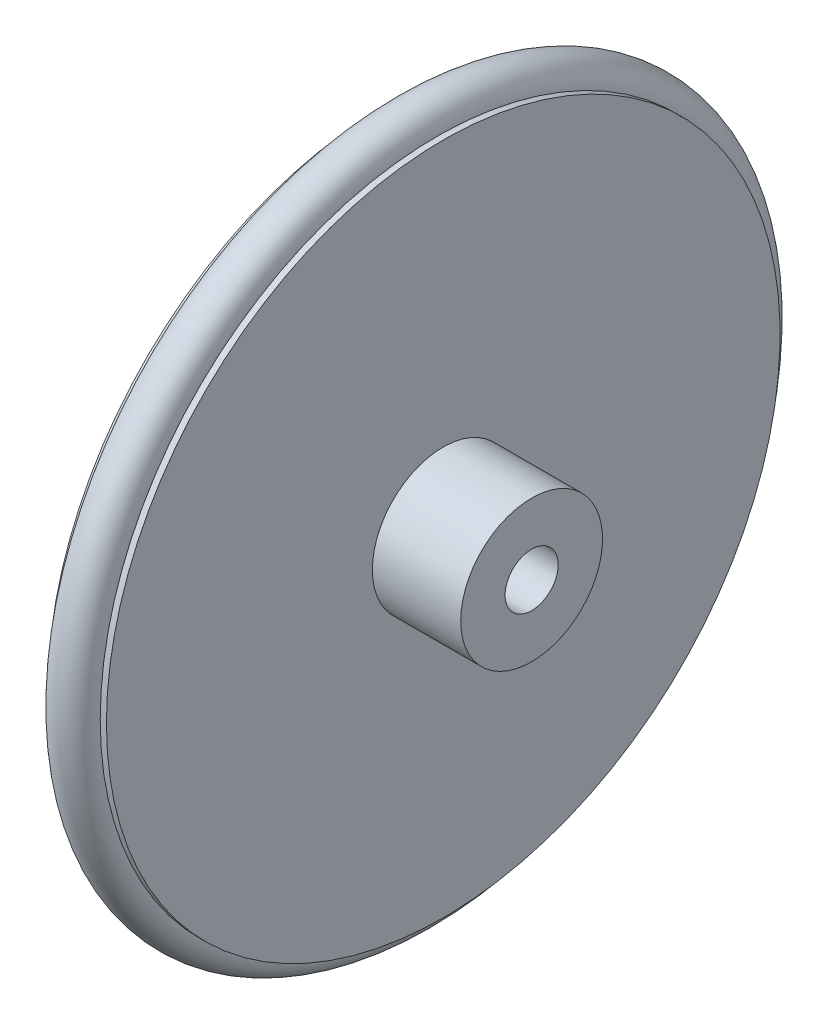
SolidWorks part; units mm, degrees
ref_plane "Plan de face" through (0, 0, 0) normal (0, 0, 1) x (1, 0, 0)
ref_plane "Plan de dessus" through (0, 0, 0) normal (0, 1, 0) x (1, 0, 0)
ref_plane "Plan de droite" through (0, 0, 0) normal (1, 0, 0) x (0, 0, -1)
sketch "Esquisse1" plane through (0, 0, 0) normal (0, 0, 1) x (1, 0, 0)
  line L0 (0, 0) -> (16.57, 0)
  line L1 (16.57, 0) -> (16.57, 8)
  line L2 (16.57, 8) -> (6.6, 8)
  line L3 (6.6, 8) -> (6.6, 38)
  line L4 (6.6, 38) -> (5.9, 38)
  line L5 (5.9, 38) -> (5.9, 35)
  line L6 (5.9, 35) -> (0.7, 35)
  line L7 (0.7, 35) -> (0.7, 38)
  line L8 (0.7, 38) -> (0, 38)
  line L9 (0, 38) -> (0, 0)
  line L10 (-19.9451, 0) -> (43.8468, 0) construction
  dimension "D1" = 16.57
  dimension "D2" = 0.7
  dimension "D3" = 0.7
  dimension "D4" = 6.6
  dimension "D5" = 3
  dimension "D6" = 8
  dimension "D7" = 38
  dimension "D8" = 38
revolve "Révolution1" add sketch "Esquisse1" angle 360 about L10
sketch "Esquisse2" plane through (16.57, 0, 0) normal (1, 0, 0) x (0, 0, -1)
  circle A0 centre (0, 0) radius 3
  dimension "D1" = 6
extrude "Enlèv. mat.-Extru.1" cut sketch "Esquisse2" against normal through all
ref_plane "Plan1" through (3.3, 0, 0) normal (1, 0, 0) x (0, 0, -1)
sketch "Esquisse4" plane through (3.3, 0, 0) normal (1, 0, 0) x (0, 0, -1)
  circle A0 centre (0, 0) radius 38.5
  dimension "D1" = 77
sketch "Esquisse5" plane through (0, 0, 0) normal (0, 0, 1) x (1, 0, 0)
  line L0 (3.3, -38.5) -> (3.3, 38.5) construction
  line L1 (5.9, 35) -> (0.7, 35) construction
  circle A0 centre (3.3, 38) radius 2.5
  dimension "D1" = 5
  dimension "D2" = 3
sweep "Balayage1" add profiles "Esquisse5" path "Esquisse4"
move or copy body "Body-Move/Copy1" [suppressed] bodies to move or copy 102 103
